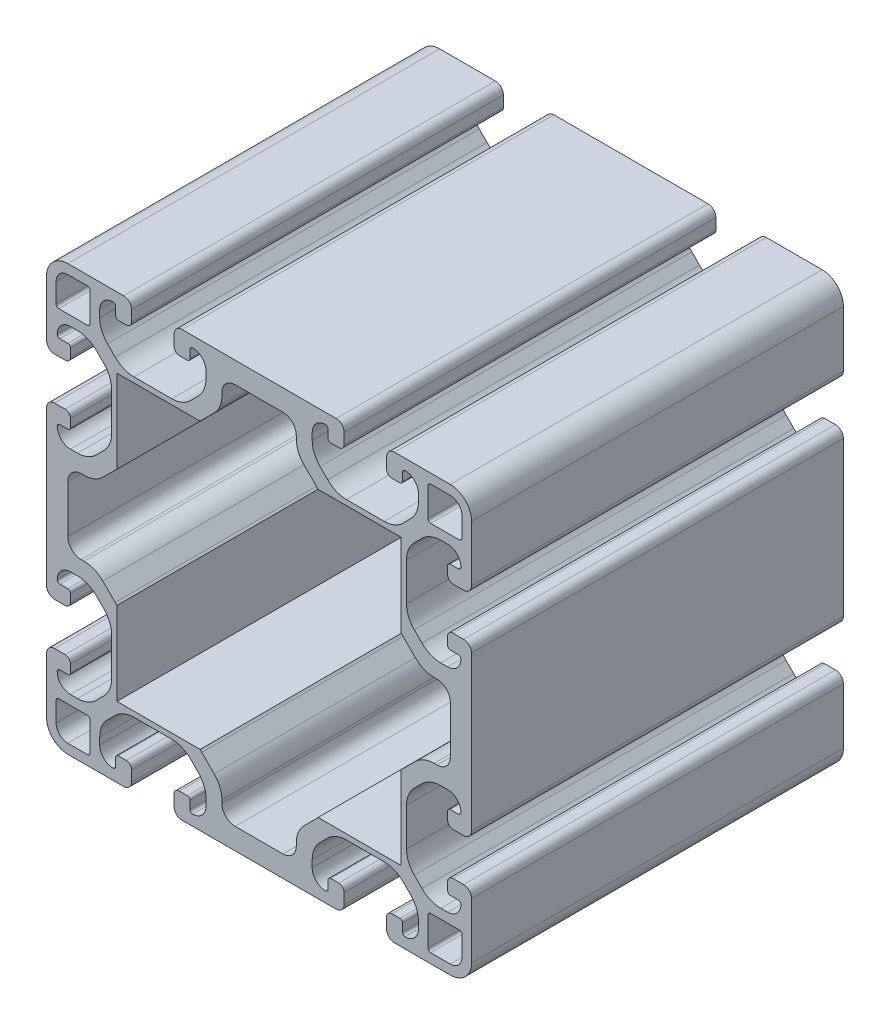
SolidWorks part; units mm, degrees
ref_plane "Plan de face" through (0, 0, 0) normal (0, 0, 1) x (1, 0, 0)
ref_plane "Plan de dessus" through (0, 0, 0) normal (0, 1, 0) x (1, 0, 0)
ref_plane "Plan de droite" through (0, 0, 0) normal (1, 0, 0) x (0, 0, -1)
ref_plane "Plan1" through (0, 0, -30) normal (0, 0, -1) x (-1, 0, 0)
sketch "Esquisse1" plane through (0, 0, -30) normal (0, 0, -1) x (-1, 0, 0)
  line L0 (-4.5, 55) -> (-4.5, 53.5)
  line L1 (-4, 53) -> (-2.5, 53)
  line L2 (-4.5, 50) -> (-5.8076, 50)
  line L3 (-9.3431, 51.4645) -> (-10.7855, 52.9069)
  line L4 (-12.25, 56.4424) -> (-12.25, 63.5576)
  line L5 (-10.7855, 67.0931) -> (-9.3431, 68.5355)
  line L6 (-5.8076, 70) -> (-4.5, 70)
  line L7 (-2.5, 67) -> (-4, 67)
  line L8 (-4.5, 66.5) -> (-4.5, 65)
  line L9 (-3.5, 64) -> (-1.5, 64)
  line L10 (0, 65.5) -> (0, 76)
  line L11 (-4, 80) -> (-14.5, 80)
  line L12 (-16, 78.5) -> (-16, 76.5)
  line L13 (-15, 75.5) -> (-13.5, 75.5)
  line L14 (-13, 76) -> (-13, 77.5)
  line L15 (-10, 75.5) -> (-10, 74.1924)
  line L16 (-11.4645, 70.6569) -> (-12.9069, 69.2145)
  line L17 (-16.4424, 67.75) -> (-23.5576, 67.75)
  line L18 (-27.0931, 69.2145) -> (-28.5355, 70.6569)
  line L19 (-30, 74.1924) -> (-30, 75.5)
  line L20 (-27, 77.5) -> (-27, 76)
  line L21 (-26.5, 75.5) -> (-25, 75.5)
  line L22 (-24, 76.5) -> (-24, 78.5)
  line L23 (-25.5, 80) -> (-54.5, 80)
  line L24 (-56, 78.5) -> (-56, 76.5)
  line L25 (-55, 75.5) -> (-53.5, 75.5)
  line L26 (-53, 76) -> (-53, 77.5)
  line L27 (-50, 75.5) -> (-50, 74.1924)
  line L28 (-51.4645, 70.6569) -> (-52.9069, 69.2145)
  line L29 (-56.4424, 67.75) -> (-63.5576, 67.75)
  line L30 (-67.0931, 69.2145) -> (-68.5355, 70.6569)
  line L31 (-70, 74.1924) -> (-70, 75.5)
  line L32 (-67, 77.5) -> (-67, 76)
  line L33 (-66.5, 75.5) -> (-65, 75.5)
  line L34 (-64, 76.5) -> (-64, 78.5)
  line L35 (-65.5, 80) -> (-76, 80)
  line L36 (-80, 76) -> (-80, 65.5)
  line L37 (-78.5, 64) -> (-76.5, 64)
  line L38 (-75.5, 65) -> (-75.5, 66.5)
  line L39 (-76, 67) -> (-77.5, 67)
  line L40 (-75.5, 70) -> (-74.1924, 70)
  line L41 (-70.6569, 68.5355) -> (-69.2145, 67.0931)
  line L42 (-67.75, 63.5576) -> (-67.75, 56.4424)
  line L43 (-69.2145, 52.9069) -> (-70.6569, 51.4645)
  line L44 (-74.1924, 50) -> (-75.5, 50)
  line L45 (-77.5, 53) -> (-76, 53)
  line L46 (-75.5, 53.5) -> (-75.5, 55)
  line L47 (-76.5, 56) -> (-78.5, 56)
  line L48 (-80, 54.5) -> (-80, 25.5)
  line L49 (-78.5, 24) -> (-76.5, 24)
  line L50 (-75.5, 25) -> (-75.5, 26.5)
  line L51 (-76, 27) -> (-77.5, 27)
  line L52 (-75.5, 30) -> (-74.1924, 30)
  line L53 (-70.6569, 28.5355) -> (-69.2145, 27.0931)
  line L54 (-67.75, 23.5576) -> (-67.75, 16.4424)
  line L55 (-69.2145, 12.9069) -> (-70.6569, 11.4645)
  line L56 (-74.1924, 10) -> (-75.5, 10)
  line L57 (-77.5, 13) -> (-76, 13)
  line L58 (-75.5, 13.5) -> (-75.5, 15)
  line L59 (-76.5, 16) -> (-78.5, 16)
  line L60 (-80, 14.5) -> (-80, 4)
  line L61 (-76, 0) -> (-65.5, 0)
  line L62 (-64, 1.5) -> (-64, 3.5)
  line L63 (-65, 4.5) -> (-66.5, 4.5)
  line L64 (-67, 4) -> (-67, 2.5)
  line L65 (-70, 4.5) -> (-70, 5.8076)
  line L66 (-68.5355, 9.3431) -> (-67.0931, 10.7855)
  line L67 (-63.5576, 12.25) -> (-56.4424, 12.25)
  line L68 (-52.9069, 10.7855) -> (-51.4645, 9.3431)
  line L69 (-50, 5.8076) -> (-50, 4.5)
  line L70 (-53, 2.5) -> (-53, 4)
  line L71 (-53.5, 4.5) -> (-55, 4.5)
  line L72 (-56, 3.5) -> (-56, 1.5)
  line L73 (-54.5, 0) -> (-25.5, 0)
  line L74 (-24, 1.5) -> (-24, 3.5)
  line L75 (-25, 4.5) -> (-26.5, 4.5)
  line L76 (-27, 4) -> (-27, 2.5)
  line L77 (-30, 4.5) -> (-30, 5.8076)
  line L78 (-28.5355, 9.3431) -> (-27.0931, 10.7855)
  line L79 (-23.5576, 12.25) -> (-16.4424, 12.25)
  line L80 (-12.9069, 10.7855) -> (-11.4645, 9.3431)
  line L81 (-10, 5.8076) -> (-10, 4.5)
  line L82 (-13, 2.5) -> (-13, 4)
  line L83 (-13.5, 4.5) -> (-15, 4.5)
  line L84 (-16, 3.5) -> (-16, 1.5)
  line L85 (-14.5, 0) -> (-4, 0)
  line L86 (0, 4) -> (0, 14.5)
  line L87 (-1.5, 16) -> (-3.5, 16)
  line L88 (-4.5, 15) -> (-4.5, 13.5)
  line L89 (-4, 13) -> (-2.5, 13)
  line L90 (-4.5, 10) -> (-5.8076, 10)
  line L91 (-9.3431, 11.4645) -> (-10.7855, 12.9069)
  line L92 (-12.25, 16.4424) -> (-12.25, 23.5576)
  line L93 (-10.7855, 27.0931) -> (-9.3431, 28.5355)
  line L94 (-5.8076, 30) -> (-4.5, 30)
  line L95 (-2.5, 27) -> (-4, 27)
  line L96 (-4.5, 26.5) -> (-4.5, 25)
  line L97 (-3.5, 24) -> (-1.5, 24)
  line L98 (0, 25.5) -> (0, 54.5)
  line L99 (-1.5, 56) -> (-3.5, 56)
  line L100 (-24.1122, 27.6036) -> (-27.6036, 24.1122)
  line L101 (-27.75, 23.7586) -> (-27.75, 16.4424)
  line L102 (-29.2145, 12.9069) -> (-31.5355, 10.5858)
  line L103 (-33, 7.0503) -> (-33, 6.5)
  line L104 (-35.5, 4) -> (-44.5, 4)
  line L105 (-47, 6.5) -> (-47, 7.0503)
  line L106 (-48.4645, 10.5858) -> (-50.7855, 12.9069)
  line L107 (-52.25, 16.4424) -> (-52.25, 23.7586)
  line L108 (-52.3964, 24.1122) -> (-55.8878, 27.6036)
  line L109 (-56.2414, 27.75) -> (-63.5576, 27.75)
  line L110 (-67.0931, 29.2145) -> (-69.4142, 31.5355)
  line L111 (-72.9497, 33) -> (-73.5, 33)
  line L112 (-76, 35.5) -> (-76, 44.5)
  line L113 (-73.5, 47) -> (-72.9497, 47)
  line L114 (-69.4142, 48.4645) -> (-67.0931, 50.7855)
  line L115 (-63.5576, 52.25) -> (-56.2414, 52.25)
  line L116 (-55.8878, 52.3964) -> (-52.3964, 55.8878)
  line L117 (-52.25, 56.2414) -> (-52.25, 63.5576)
  line L118 (-50.7855, 67.0931) -> (-48.4645, 69.4142)
  line L119 (-47, 72.9497) -> (-47, 73.5)
  line L120 (-44.5, 76) -> (-35.5, 76)
  line L121 (-33, 73.5) -> (-33, 72.9497)
  line L122 (-31.5355, 69.4142) -> (-29.2145, 67.0931)
  line L123 (-27.75, 63.5576) -> (-27.75, 56.2414)
  line L124 (-27.6036, 55.8878) -> (-24.1122, 52.3964)
  line L125 (-23.7586, 52.25) -> (-16.4424, 52.25)
  line L126 (-12.9069, 50.7855) -> (-10.5858, 48.4645)
  line L127 (-7.0503, 47) -> (-6.5, 47)
  line L128 (-4, 44.5) -> (-4, 35.5)
  line L129 (-6.5, 33) -> (-7.0503, 33)
  line L130 (-10.5858, 31.5355) -> (-12.9069, 29.2145)
  line L131 (-16.4424, 27.75) -> (-23.7586, 27.75)
  line L132 (-4, 1.8) -> (-7.7, 1.8)
  line L133 (-8.2, 2.3) -> (-8.2, 7.7)
  line L134 (-7.7, 8.2) -> (-2.3, 8.2)
  line L135 (-1.8, 7.7) -> (-1.8, 4)
  line L136 (-78.2, 4) -> (-78.2, 7.7)
  line L137 (-77.7, 8.2) -> (-72.3, 8.2)
  line L138 (-71.8, 7.7) -> (-71.8, 2.3)
  line L139 (-72.3, 1.8) -> (-76, 1.8)
  line L140 (-76, 78.2) -> (-72.3, 78.2)
  line L141 (-71.8, 77.7) -> (-71.8, 72.3)
  line L142 (-72.3, 71.8) -> (-77.7, 71.8)
  line L143 (-78.2, 72.3) -> (-78.2, 76)
  line L144 (-1.8, 76) -> (-1.8, 72.3)
  line L145 (-2.3, 71.8) -> (-7.7, 71.8)
  line L146 (-8.2, 72.3) -> (-8.2, 77.7)
  line L147 (-7.7, 78.2) -> (-4, 78.2)
  arc A0 (-4.5, 53.5) -> (-4, 53) centre (-4, 53.5) ccw
  arc A1 (-2.5, 53) -> (-2, 52.5) centre (-2.5, 52.5) cw
  arc A2 (-2, 52.5) -> (-4.5, 50) centre (-4.5, 52.5) cw
  arc A3 (-5.8076, 50) -> (-9.3431, 51.4645) centre (-5.8076, 55) cw
  arc A4 (-10.7855, 52.9069) -> (-12.25, 56.4424) centre (-7.25, 56.4424) cw
  arc A5 (-12.25, 63.5576) -> (-10.7855, 67.0931) centre (-7.25, 63.5576) cw
  arc A6 (-9.3431, 68.5355) -> (-5.8076, 70) centre (-5.8076, 65) cw
  arc A7 (-4.5, 70) -> (-2, 67.5) centre (-4.5, 67.5) cw
  arc A8 (-2, 67.5) -> (-2.5, 67) centre (-2.5, 67.5) cw
  arc A9 (-4, 67) -> (-4.5, 66.5) centre (-4, 66.5) ccw
  arc A10 (-4.5, 65) -> (-3.5, 64) centre (-3.5, 65) ccw
  arc A11 (-1.5, 64) -> (0, 65.5) centre (-1.5, 65.5) ccw
  arc A12 (0, 76) -> (-4, 80) centre (-4, 76) ccw
  arc A13 (-14.5, 80) -> (-16, 78.5) centre (-14.5, 78.5) ccw
  arc A14 (-16, 76.5) -> (-15, 75.5) centre (-15, 76.5) ccw
  arc A15 (-13.5, 75.5) -> (-13, 76) centre (-13.5, 76) ccw
  arc A16 (-13, 77.5) -> (-12.5, 78) centre (-12.5, 77.5) cw
  arc A17 (-12.5, 78) -> (-10, 75.5) centre (-12.5, 75.5) cw
  arc A18 (-10, 74.1924) -> (-11.4645, 70.6569) centre (-15, 74.1924) cw
  arc A19 (-12.9069, 69.2145) -> (-16.4424, 67.75) centre (-16.4424, 72.75) cw
  arc A20 (-23.5576, 67.75) -> (-27.0931, 69.2145) centre (-23.5576, 72.75) cw
  arc A21 (-28.5355, 70.6569) -> (-30, 74.1924) centre (-25, 74.1924) cw
  arc A22 (-30, 75.5) -> (-27.5, 78) centre (-27.5, 75.5) cw
  arc A23 (-27.5, 78) -> (-27, 77.5) centre (-27.5, 77.5) cw
  arc A24 (-27, 76) -> (-26.5, 75.5) centre (-26.5, 76) ccw
  arc A25 (-25, 75.5) -> (-24, 76.5) centre (-25, 76.5) ccw
  arc A26 (-24, 78.5) -> (-25.5, 80) centre (-25.5, 78.5) ccw
  arc A27 (-54.5, 80) -> (-56, 78.5) centre (-54.5, 78.5) ccw
  arc A28 (-56, 76.5) -> (-55, 75.5) centre (-55, 76.5) ccw
  arc A29 (-53.5, 75.5) -> (-53, 76) centre (-53.5, 76) ccw
  arc A30 (-53, 77.5) -> (-52.5, 78) centre (-52.5, 77.5) cw
  arc A31 (-52.5, 78) -> (-50, 75.5) centre (-52.5, 75.5) cw
  arc A32 (-50, 74.1924) -> (-51.4645, 70.6569) centre (-55, 74.1924) cw
  arc A33 (-52.9069, 69.2145) -> (-56.4424, 67.75) centre (-56.4424, 72.75) cw
  arc A34 (-63.5576, 67.75) -> (-67.0931, 69.2145) centre (-63.5576, 72.75) cw
  arc A35 (-68.5355, 70.6569) -> (-70, 74.1924) centre (-65, 74.1924) cw
  arc A36 (-70, 75.5) -> (-67.5, 78) centre (-67.5, 75.5) cw
  arc A37 (-67.5, 78) -> (-67, 77.5) centre (-67.5, 77.5) cw
  arc A38 (-67, 76) -> (-66.5, 75.5) centre (-66.5, 76) ccw
  arc A39 (-65, 75.5) -> (-64, 76.5) centre (-65, 76.5) ccw
  arc A40 (-64, 78.5) -> (-65.5, 80) centre (-65.5, 78.5) ccw
  arc A41 (-76, 80) -> (-80, 76) centre (-76, 76) ccw
  arc A42 (-80, 65.5) -> (-78.5, 64) centre (-78.5, 65.5) ccw
  arc A43 (-76.5, 64) -> (-75.5, 65) centre (-76.5, 65) ccw
  arc A44 (-75.5, 66.5) -> (-76, 67) centre (-76, 66.5) ccw
  arc A45 (-77.5, 67) -> (-78, 67.5) centre (-77.5, 67.5) cw
  arc A46 (-78, 67.5) -> (-75.5, 70) centre (-75.5, 67.5) cw
  arc A47 (-74.1924, 70) -> (-70.6569, 68.5355) centre (-74.1924, 65) cw
  arc A48 (-69.2145, 67.0931) -> (-67.75, 63.5576) centre (-72.75, 63.5576) cw
  arc A49 (-67.75, 56.4424) -> (-69.2145, 52.9069) centre (-72.75, 56.4424) cw
  arc A50 (-70.6569, 51.4645) -> (-74.1924, 50) centre (-74.1924, 55) cw
  arc A51 (-75.5, 50) -> (-78, 52.5) centre (-75.5, 52.5) cw
  arc A52 (-78, 52.5) -> (-77.5, 53) centre (-77.5, 52.5) cw
  arc A53 (-76, 53) -> (-75.5, 53.5) centre (-76, 53.5) ccw
  arc A54 (-75.5, 55) -> (-76.5, 56) centre (-76.5, 55) ccw
  arc A55 (-78.5, 56) -> (-80, 54.5) centre (-78.5, 54.5) ccw
  arc A56 (-80, 25.5) -> (-78.5, 24) centre (-78.5, 25.5) ccw
  arc A57 (-76.5, 24) -> (-75.5, 25) centre (-76.5, 25) ccw
  arc A58 (-75.5, 26.5) -> (-76, 27) centre (-76, 26.5) ccw
  arc A59 (-77.5, 27) -> (-78, 27.5) centre (-77.5, 27.5) cw
  arc A60 (-78, 27.5) -> (-75.5, 30) centre (-75.5, 27.5) cw
  arc A61 (-74.1924, 30) -> (-70.6569, 28.5355) centre (-74.1924, 25) cw
  arc A62 (-69.2145, 27.0931) -> (-67.75, 23.5576) centre (-72.75, 23.5576) cw
  arc A63 (-67.75, 16.4424) -> (-69.2145, 12.9069) centre (-72.75, 16.4424) cw
  arc A64 (-70.6569, 11.4645) -> (-74.1924, 10) centre (-74.1924, 15) cw
  arc A65 (-75.5, 10) -> (-78, 12.5) centre (-75.5, 12.5) cw
  arc A66 (-78, 12.5) -> (-77.5, 13) centre (-77.5, 12.5) cw
  arc A67 (-76, 13) -> (-75.5, 13.5) centre (-76, 13.5) ccw
  arc A68 (-75.5, 15) -> (-76.5, 16) centre (-76.5, 15) ccw
  arc A69 (-78.5, 16) -> (-80, 14.5) centre (-78.5, 14.5) ccw
  arc A70 (-80, 4) -> (-76, 0) centre (-76, 4) ccw
  arc A71 (-65.5, 0) -> (-64, 1.5) centre (-65.5, 1.5) ccw
  arc A72 (-64, 3.5) -> (-65, 4.5) centre (-65, 3.5) ccw
  arc A73 (-66.5, 4.5) -> (-67, 4) centre (-66.5, 4) ccw
  arc A74 (-67, 2.5) -> (-67.5, 2) centre (-67.5, 2.5) cw
  arc A75 (-67.5, 2) -> (-70, 4.5) centre (-67.5, 4.5) cw
  arc A76 (-70, 5.8076) -> (-68.5355, 9.3431) centre (-65, 5.8076) cw
  arc A77 (-67.0931, 10.7855) -> (-63.5576, 12.25) centre (-63.5576, 7.25) cw
  arc A78 (-56.4424, 12.25) -> (-52.9069, 10.7855) centre (-56.4424, 7.25) cw
  arc A79 (-51.4645, 9.3431) -> (-50, 5.8076) centre (-55, 5.8076) cw
  arc A80 (-50, 4.5) -> (-52.5, 2) centre (-52.5, 4.5) cw
  arc A81 (-52.5, 2) -> (-53, 2.5) centre (-52.5, 2.5) cw
  arc A82 (-53, 4) -> (-53.5, 4.5) centre (-53.5, 4) ccw
  arc A83 (-55, 4.5) -> (-56, 3.5) centre (-55, 3.5) ccw
  arc A84 (-56, 1.5) -> (-54.5, 0) centre (-54.5, 1.5) ccw
  arc A85 (-25.5, 0) -> (-24, 1.5) centre (-25.5, 1.5) ccw
  arc A86 (-24, 3.5) -> (-25, 4.5) centre (-25, 3.5) ccw
  arc A87 (-26.5, 4.5) -> (-27, 4) centre (-26.5, 4) ccw
  arc A88 (-27, 2.5) -> (-27.5, 2) centre (-27.5, 2.5) cw
  arc A89 (-27.5, 2) -> (-30, 4.5) centre (-27.5, 4.5) cw
  arc A90 (-30, 5.8076) -> (-28.5355, 9.3431) centre (-25, 5.8076) cw
  arc A91 (-27.0931, 10.7855) -> (-23.5576, 12.25) centre (-23.5576, 7.25) cw
  arc A92 (-16.4424, 12.25) -> (-12.9069, 10.7855) centre (-16.4424, 7.25) cw
  arc A93 (-11.4645, 9.3431) -> (-10, 5.8076) centre (-15, 5.8076) cw
  arc A94 (-10, 4.5) -> (-12.5, 2) centre (-12.5, 4.5) cw
  arc A95 (-12.5, 2) -> (-13, 2.5) centre (-12.5, 2.5) cw
  arc A96 (-13, 4) -> (-13.5, 4.5) centre (-13.5, 4) ccw
  arc A97 (-15, 4.5) -> (-16, 3.5) centre (-15, 3.5) ccw
  arc A98 (-16, 1.5) -> (-14.5, 0) centre (-14.5, 1.5) ccw
  arc A99 (-4, 0) -> (0, 4) centre (-4, 4) ccw
  arc A100 (0, 14.5) -> (-1.5, 16) centre (-1.5, 14.5) ccw
  arc A101 (-3.5, 16) -> (-4.5, 15) centre (-3.5, 15) ccw
  arc A102 (-4.5, 13.5) -> (-4, 13) centre (-4, 13.5) ccw
  arc A103 (-2.5, 13) -> (-2, 12.5) centre (-2.5, 12.5) cw
  arc A104 (-2, 12.5) -> (-4.5, 10) centre (-4.5, 12.5) cw
  arc A105 (-5.8076, 10) -> (-9.3431, 11.4645) centre (-5.8076, 15) cw
  arc A106 (-10.7855, 12.9069) -> (-12.25, 16.4424) centre (-7.25, 16.4424) cw
  arc A107 (-12.25, 23.5576) -> (-10.7855, 27.0931) centre (-7.25, 23.5576) cw
  arc A108 (-9.3431, 28.5355) -> (-5.8076, 30) centre (-5.8076, 25) cw
  arc A109 (-4.5, 30) -> (-2, 27.5) centre (-4.5, 27.5) cw
  arc A110 (-2, 27.5) -> (-2.5, 27) centre (-2.5, 27.5) cw
  arc A111 (-4, 27) -> (-4.5, 26.5) centre (-4, 26.5) ccw
  arc A112 (-4.5, 25) -> (-3.5, 24) centre (-3.5, 25) ccw
  arc A113 (-1.5, 24) -> (0, 25.5) centre (-1.5, 25.5) ccw
  arc A114 (0, 54.5) -> (-1.5, 56) centre (-1.5, 54.5) ccw
  arc A115 (-3.5, 56) -> (-4.5, 55) centre (-3.5, 55) ccw
  circle A116 centre (-20, 20) radius 3.4
  circle A117 centre (-20, 60) radius 3.4
  circle A118 centre (-60, 20) radius 3.4
  circle A119 centre (-60, 60) radius 3.4
  arc A120 (-23.7586, 27.75) -> (-24.1122, 27.6036) centre (-23.7586, 27.25) ccw
  arc A121 (-27.6036, 24.1122) -> (-27.75, 23.7586) centre (-27.25, 23.7586) ccw
  arc A122 (-27.75, 16.4424) -> (-29.2145, 12.9069) centre (-32.75, 16.4424) cw
  arc A123 (-31.5355, 10.5858) -> (-33, 7.0503) centre (-28, 7.0503) ccw
  arc A124 (-33, 6.5) -> (-35.5, 4) centre (-35.5, 6.5) cw
  arc A125 (-44.5, 4) -> (-47, 6.5) centre (-44.5, 6.5) cw
  arc A126 (-47, 7.0503) -> (-48.4645, 10.5858) centre (-52, 7.0503) ccw
  arc A127 (-50.7855, 12.9069) -> (-52.25, 16.4424) centre (-47.25, 16.4424) cw
  arc A128 (-52.25, 23.7586) -> (-52.3964, 24.1122) centre (-52.75, 23.7586) ccw
  arc A129 (-55.8878, 27.6036) -> (-56.2414, 27.75) centre (-56.2414, 27.25) ccw
  arc A130 (-63.5576, 27.75) -> (-67.0931, 29.2145) centre (-63.5576, 32.75) cw
  arc A131 (-69.4142, 31.5355) -> (-72.9497, 33) centre (-72.9497, 28) ccw
  arc A132 (-73.5, 33) -> (-76, 35.5) centre (-73.5, 35.5) cw
  arc A133 (-76, 44.5) -> (-73.5, 47) centre (-73.5, 44.5) cw
  arc A134 (-72.9497, 47) -> (-69.4142, 48.4645) centre (-72.9497, 52) ccw
  arc A135 (-67.0931, 50.7855) -> (-63.5576, 52.25) centre (-63.5576, 47.25) cw
  arc A136 (-56.2414, 52.25) -> (-55.8878, 52.3964) centre (-56.2414, 52.75) ccw
  arc A137 (-52.3964, 55.8878) -> (-52.25, 56.2414) centre (-52.75, 56.2414) ccw
  arc A138 (-52.25, 63.5576) -> (-50.7855, 67.0931) centre (-47.25, 63.5576) cw
  arc A139 (-48.4645, 69.4142) -> (-47, 72.9497) centre (-52, 72.9497) ccw
  arc A140 (-47, 73.5) -> (-44.5, 76) centre (-44.5, 73.5) cw
  arc A141 (-35.5, 76) -> (-33, 73.5) centre (-35.5, 73.5) cw
  arc A142 (-33, 72.9497) -> (-31.5355, 69.4142) centre (-28, 72.9497) ccw
  arc A143 (-29.2145, 67.0931) -> (-27.75, 63.5576) centre (-32.75, 63.5576) cw
  arc A144 (-27.75, 56.2414) -> (-27.6036, 55.8878) centre (-27.25, 56.2414) ccw
  arc A145 (-24.1122, 52.3964) -> (-23.7586, 52.25) centre (-23.7586, 52.75) ccw
  arc A146 (-16.4424, 52.25) -> (-12.9069, 50.7855) centre (-16.4424, 47.25) cw
  arc A147 (-10.5858, 48.4645) -> (-7.0503, 47) centre (-7.0503, 52) ccw
  arc A148 (-6.5, 47) -> (-4, 44.5) centre (-6.5, 44.5) cw
  arc A149 (-4, 35.5) -> (-6.5, 33) centre (-6.5027, 35.5027) cw
  arc A150 (-7.0503, 33) -> (-10.5858, 31.5355) centre (-7.0503, 28) ccw
  arc A151 (-12.9069, 29.2145) -> (-16.4424, 27.75) centre (-16.4424, 32.75) cw
  arc A152 (-1.8, 4) -> (-4, 1.8) centre (-4, 4) cw
  arc A153 (-7.7, 1.8) -> (-8.2, 2.3) centre (-7.7, 2.3) cw
  arc A154 (-8.2, 7.7) -> (-7.7, 8.2) centre (-7.7, 7.7) cw
  arc A155 (-2.3, 8.2) -> (-1.8, 7.7) centre (-2.3, 7.7) cw
  arc A156 (-76, 1.8) -> (-78.2, 4) centre (-76, 4) cw
  arc A157 (-78.2, 7.7) -> (-77.7, 8.2) centre (-77.7, 7.7) cw
  arc A158 (-72.3, 8.2) -> (-71.8, 7.7) centre (-72.3, 7.7) cw
  arc A159 (-71.8, 2.3) -> (-72.3, 1.8) centre (-72.3, 2.3) cw
  arc A160 (-78.2, 76) -> (-76, 78.2) centre (-76, 76) cw
  arc A161 (-72.3, 78.2) -> (-71.8, 77.7) centre (-72.3, 77.7) cw
  arc A162 (-71.8, 72.3) -> (-72.3, 71.8) centre (-72.3, 72.3) cw
  arc A163 (-77.7, 71.8) -> (-78.2, 72.3) centre (-77.7, 72.3) cw
  arc A164 (-4, 78.2) -> (-1.8, 76) centre (-4, 76) cw
  arc A165 (-1.8, 72.3) -> (-2.3, 71.8) centre (-2.3, 72.3) cw
  arc A166 (-7.7, 71.8) -> (-8.2, 72.3) centre (-7.7, 72.3) cw
  arc A167 (-8.2, 77.7) -> (-7.7, 78.2) centre (-7.7, 77.7) cw
extrude "Boss.-Extru.1" add sketch "Esquisse1" against normal blind 70
sketch "Esquisse2" plane through (0, 0, 40) normal (0, 0, 1) x (1, 0, 0)
  line L0 (4, 40) -> (76, 40) construction
  line L1 (4, 35.5) -> (4, 44.5) construction
  line L2 (76, 44.5) -> (76, 35.5) construction
  line L3 (40, 76) -> (40, -2.6712) construction
  line L4 (35.5, 76) -> (44.5, 76) construction
  line L5 (12.25, 56.4424) -> (12.25, 63.5576) construction
  line L6 (13.25, 13.25) -> (66.75, 13.25)
  line L7 (13.25, 13.25) -> (13.25, 66.75)
  line L8 (13.25, 66.75) -> (66.75, 66.75)
  line L9 (66.75, 13.25) -> (66.75, 66.75)
  line L10 (13.25, 13.25) -> (66.75, 66.75) construction
  line L11 (13.25, 66.75) -> (66.75, 13.25) construction
  line L12 (16.4424, 67.75) -> (23.5576, 67.75) construction
  point P10 (40, 40)
  dimension "D1" = 1
  dimension "D2" = 1
extrude "Enlèv. mat.-Extru.1" cut sketch "Esquisse2" against normal blind 65
